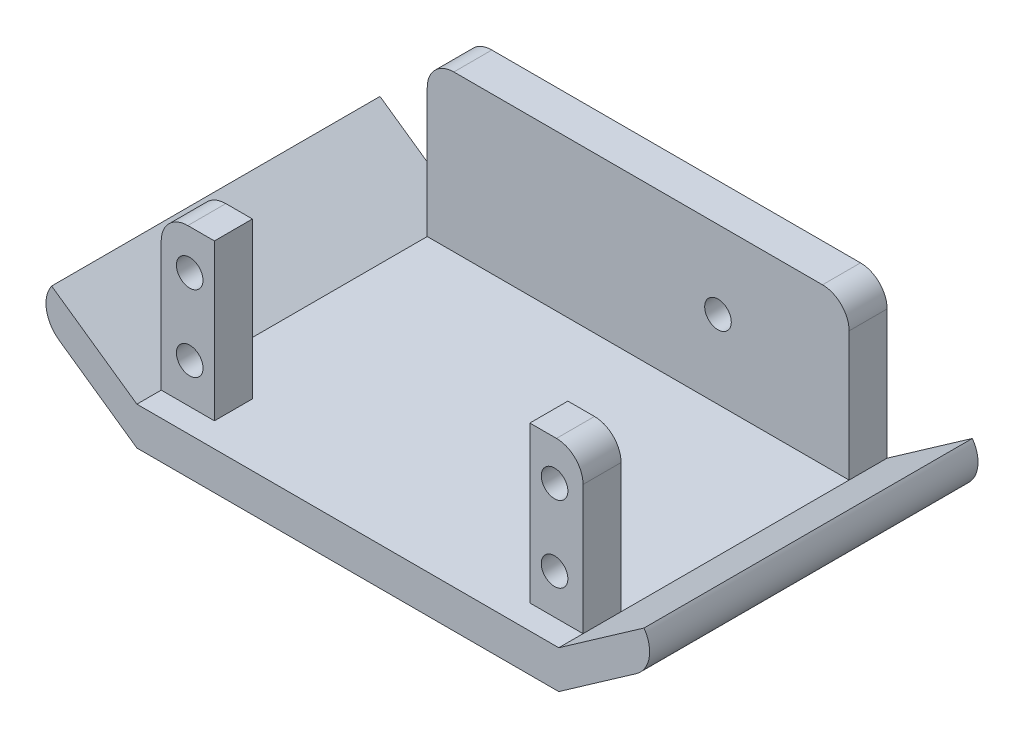
SolidWorks part; units mm, degrees
ref_plane "Front" through (0, 0, 0) normal (0, 0, 1) x (1, 0, 0)
ref_plane "Top" through (0, 0, 0) normal (0, 1, 0) x (1, 0, 0)
ref_plane "Right" through (0, 0, 0) normal (1, 0, 0) x (0, 0, -1)
sketch "Sketch1" plane through (0, 0, 0) normal (0, 1, 0) x (1, 0, 0)
  line L1 (0, 0) -> (55.5, 0)
  line L2 (0, 0) -> (0, 43.2)
  line L3 (0, 43.2) -> (55.5, 43.2)
  line L4 (55.5, 0) -> (55.5, 43.2)
  dimension "D1" = 55.5
  dimension "D2" = 43.2
extrude "base" add sketch "Sketch1" along normal blind 5
sketch "Sketch2" plane through (0, 0, -43.2) normal (0, 0, -1) x (-1, 0, 0)
  line L1 (0, 5) -> (0, 0) construction
  line L2 (-55.5, 0) -> (0, 0)
  line L3 (-55.5, 0) -> (-55.5, 25.5)
  line L4 (-55.5, 25.5) -> (0, 25.5)
  line L5 (0, 0) -> (0, 25.5)
  line L6 (-55.5, 5) -> (0, 5) construction
  dimension "D1" = 20.5
extrude "wall" add sketch "Sketch2" against normal blind 5
ref_plane "Plane1" through (0, 0, -8.2) normal (0, 0, 1) x (1, 0, 0)
sketch "Sketch3" plane through (0, 0, -8.2) normal (0, 0, 1) x (1, 0, 0)
  line L0 (0, 5) -> (55.5, 5) construction
  line L1 (0, 25.5) -> (7, 25.5)
  line L2 (0, 25.5) -> (0, 5)
  line L3 (0, 5) -> (7, 5)
  line L4 (7, 25.5) -> (7, 5)
  line L5 (27.75, 5) -> (27.75, 25.5) construction
  line L6 (55.5, 5) -> (0, 5) construction
  line L7 (0, 25.5) -> (55.5, 25.5) construction
  line L8 (55.5, 5) -> (48.5, 5)
  line L9 (48.5, 25.5) -> (48.5, 5)
  line L10 (55.5, 25.5) -> (48.5, 25.5)
  line L11 (55.5, 25.5) -> (55.5, 5)
  dimension "D1" = 7
extrude "mountingTabs" add sketch "Sketch3" along normal blind 5
sketch "Sketch4" plane through (0, 0, 0) normal (0, 0, 1) x (1, 0, 0)
  line L0 (27.75, 0) -> (27.75, 25.5) construction
  line L1 (0, 0) -> (55.5, 0) construction
  line L2 (0, 25.5) -> (55.5, 25.5) construction
  line L3 (0, 0) -> (-10.2089, 7.1483)
  line L4 (0, 5) -> (-11.2182, 12.8551)
  line L5 (0, 5) -> (0, 0)
  line L6 (55.5, 5) -> (66.7182, 12.8551)
  line L7 (55.5, 5) -> (55.5, 0)
  line L8 (55.5, 0) -> (65.7089, 7.1483)
  arc A0 (-11.2182, 12.8551) -> (-10.2089, 7.1483) centre (-7.8572, 10.5069) ccw
  arc A1 (66.7182, 12.8551) -> (65.7089, 7.1483) centre (63.3572, 10.5069) cw
  dimension "D1" = 145
  dimension "D2" = 12.4627
  dimension "D3" = 13.6949
extrude "lips" add sketch "Sketch4" against normal up to surface (43.2 mm away) up to face at (27.75, 12.75, -43.2)
sketch "Sketch5" plane through (0, 0, -3.2) normal (0, 0, 1) x (1, 0, 0)
  line L0 (27.75, 0) -> (27.75, 25.5) construction
  line L3 (0, 15.25) -> (55.5, 15.25) construction
  line L4 (0, 25.5) -> (0, 5) construction
  line L5 (55.5, 5) -> (55.5, 25.5) construction
  line L6 (7, 25.5) -> (0, 25.5) construction
  line L7 (0, 0) -> (55.5, 0) construction
  line L8 (0, 25.5) -> (55.5, 25.5) construction
  circle A0 centre (3.75, 20.25) radius 1.75
  circle A1 centre (3.75, 10.25) radius 1.75
  circle A4 centre (51.75, 10.25) radius 1.75
  circle A5 centre (51.75, 20.25) radius 1.75
  dimension "D1" = 3.5
  dimension "D2" = 5.25
  dimension "D3" = 3.75
extrude "mountingHoles" cut sketch "Sketch5" against normal blind 5
fillet "fillets" radius 3.5 4 edges at (55.5, 25.5, -40.7) (55.5, 25.5, -5.7) (0, 25.5, -40.7) (0, 25.5, -5.7)
sketch "Sketch6" plane through (0, 0, -38.2) normal (0, 0, 1) x (1, 0, 0)
  line L0 (3.5, 25.5) -> (52, 25.5) construction
  line L1 (55.5, 5) -> (55.5, 22) construction
  circle A0 centre (38.25, 15.25) radius 1.75
  dimension "D1" = 3.5
  dimension "D2" = 10.25
  dimension "D3" = 17.25
extrude "throughHole" cut sketch "Sketch6" against normal blind 5
